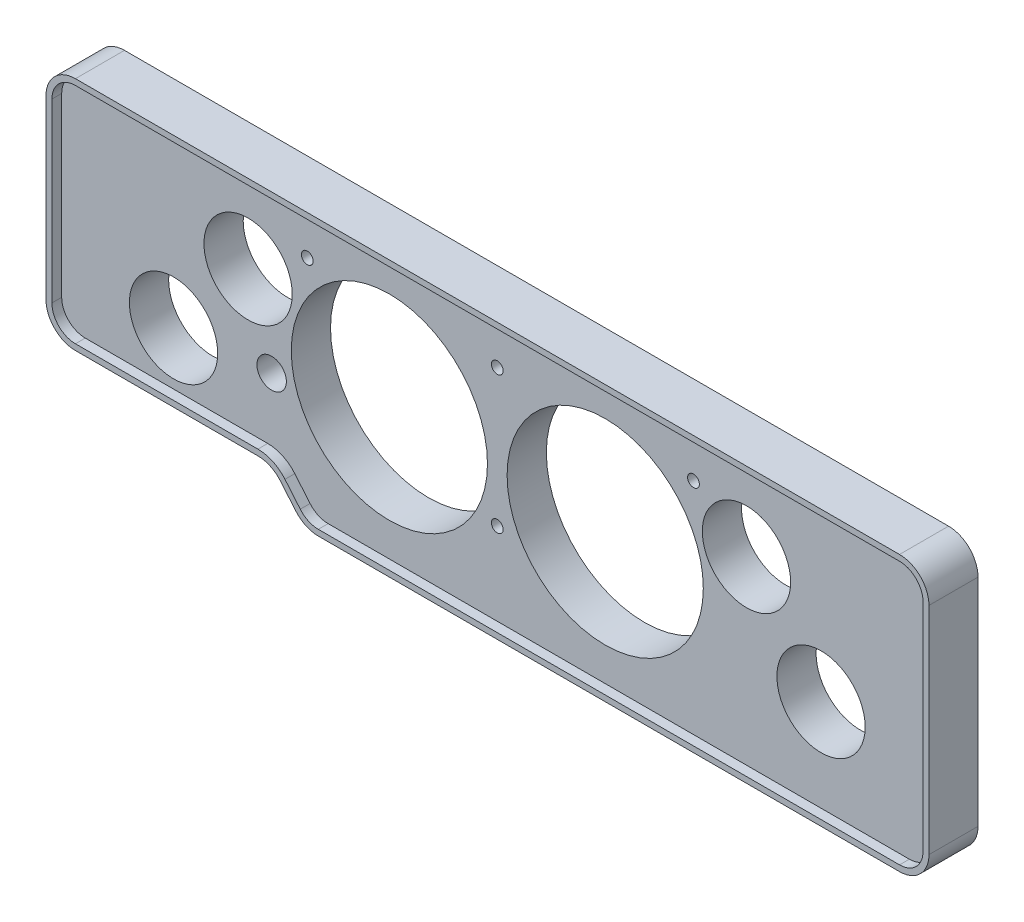
SolidWorks part; units mm, degrees
ref_plane "Front Plane" through (0, 0, 0) normal (0, 0, 1) x (1, 0, 0)
ref_plane "Top Plane" through (0, 0, 0) normal (0, 1, 0) x (1, 0, 0)
ref_plane "Right Plane" through (0, 0, 0) normal (1, 0, 0) x (0, 0, -1)
sketch "Sketch1" plane through (0, 0, 0) normal (0, 0, 1) x (1, 0, 0)
  line L0 (-225, -50) -> (-110, -50)
  line L1 (-225, 70) -> (225, 70)
  line L2 (-225, 70) -> (-225, -50)
  line L3 (-93.218, -70) -> (225, -70)
  line L4 (225, 70) -> (225, -70)
  line L5 (-225, 70) -> (225, -70) construction
  line L6 (-225, -70) -> (225, 70) construction
  line L7 (-110, -50) -> (-93.218, -70)
  point P0 (0, 0)
  dimension "D1" = 140
  dimension "D2" = 450
  dimension "D3" = 20
  dimension "D4" = 115
  dimension "D5" = 130
extrude "Boss-Extrude1" add sketch "Sketch1" against normal blind 25
fillet "Fillet1" radius 15 6 edges at (-110, -50, -12.5) (-93.218, -70, -12.5) (225, -70, -12.5) (225, 70, -12.5) (-225, 70, -12.5) (-225, -50, -12.5)
sketch "Sketch2" plane through (0, 0, 0) normal (0, 0, 1) x (1, 0, 0)
  line L0 (0, 0) -> (0, 46.4629) construction
  circle A0 centre (55, 0) radius 50
  circle A1 centre (127, 25) radius 22.5
  circle A2 centre (165, -20) radius 22.5
  circle A3 centre (-165, -20) radius 22.5
  circle A4 centre (-127, 25) radius 22.5
  circle A5 centre (-55, 0) radius 50
  circle A6 centre (-115, -15) radius 7.5
  circle A7 centre (-115, -15) radius 12.5 construction
  dimension "D1" = 100
  dimension "D2" = 55
  dimension "D3" = 45
  dimension "D6" = 45
  dimension "D9" = 15
  dimension "D12" = 25
  dimension "D4" = 25
  dimension "D5" = 127
  dimension "D7" = 165
  dimension "D8" = 20
  dimension "D10" = 15
  dimension "D11" = 115
extrude "Cut-Extrude1" cut sketch "Sketch2" against normal through all
sketch "Sketch4" plane through (0, 0, 0) normal (0, 0, 1) x (1, 0, 0)
  line L12 (-103.2058, -53.4298) -> (-95.4159, -62.7135)
  line L13 (-86.2234, -67) -> (210, -67)
  line L14 (222, -55) -> (222, 55)
  line L15 (210, 67) -> (-210, 67)
  line L16 (-222, 55) -> (-222, -35)
  line L17 (-210, -47) -> (-116.9946, -47)
  line L18 (-103.2058, -53.4298) -> (-95.4159, -62.7135)
  line L19 (-86.2234, -67) -> (210, -67)
  line L20 (222, -55) -> (222, 55)
  line L21 (210, 67) -> (-210, 67)
  line L22 (-222, 55) -> (-222, -35)
  line L23 (-210, -47) -> (-116.9946, -47)
  arc A12 (-95.4159, -62.7135) -> (-86.2234, -67) centre (-86.2234, -55) ccw
  arc A13 (210, -67) -> (222, -55) centre (210, -55) ccw
  arc A14 (222, 55) -> (210, 67) centre (210, 55) ccw
  arc A15 (-210, 67) -> (-222, 55) centre (-210, 55) ccw
  arc A16 (-222, -35) -> (-210, -47) centre (-210, -35) ccw
  arc A17 (-103.2058, -53.4298) -> (-116.9946, -47) centre (-116.9946, -65) ccw
  arc A18 (-95.4159, -62.7135) -> (-86.2234, -67) centre (-86.2234, -55) ccw
  arc A19 (210, -67) -> (222, -55) centre (210, -55) ccw
  arc A20 (222, 55) -> (210, 67) centre (210, 55) ccw
  arc A21 (-210, 67) -> (-222, 55) centre (-210, 55) ccw
  arc A22 (-222, -35) -> (-210, -47) centre (-210, -35) ccw
  arc A23 (-103.2058, -53.4298) -> (-116.9946, -47) centre (-116.9946, -65) ccw
  dimension "D1" = 3
extrude "Cut-Extrude2" cut sketch "Sketch4" against normal blind 5
sketch "Sketch5" plane through (0, 0, -5) normal (0, 0, 1) x (1, 0, 0)
  line L0 (-96.85, 45) -> (0, 45) construction
  line L1 (0, 45) -> (100, 45) construction
  line L2 (0, 45) -> (0, -25) construction
  circle A0 centre (0, 45) radius 3
  circle A1 centre (0, -25) radius 3
  circle A2 centre (100, 45) radius 3
  circle A3 centre (-96.85, 45) radius 3
  dimension "D1" = 6
  dimension "D2" = 196.85
  dimension "D3" = 100
  dimension "D4" = 45
  dimension "D5" = 25
extrude "Cut-Extrude3" cut sketch "Sketch5" against normal blind 12.7
